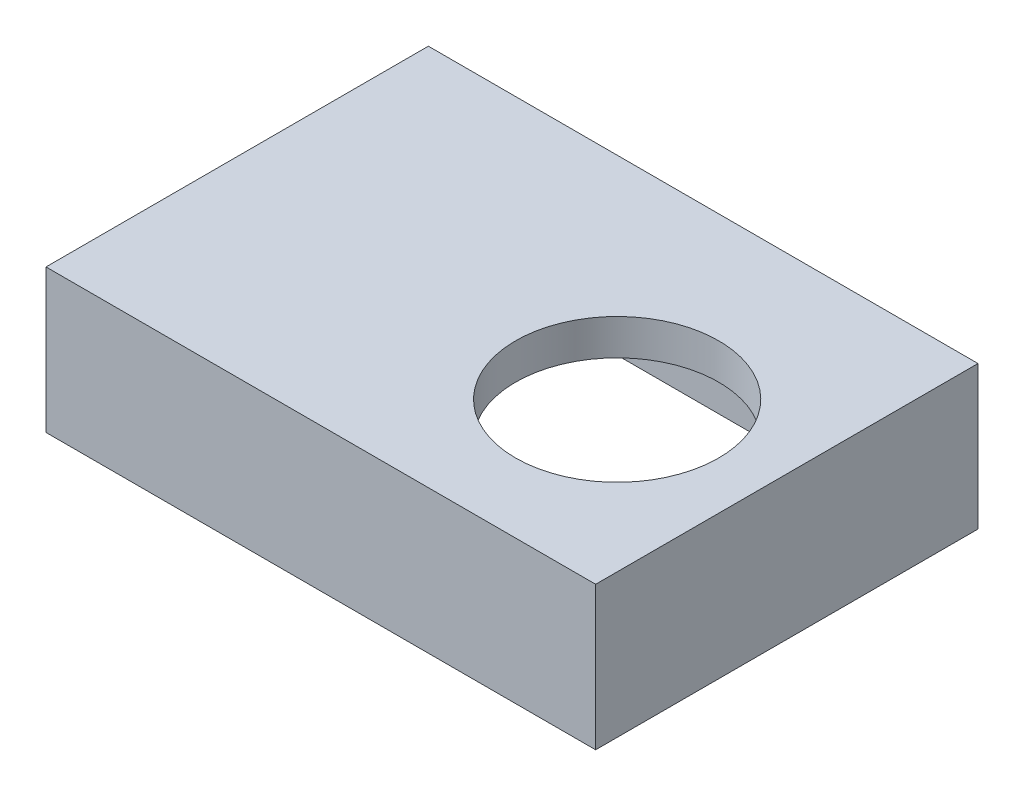
SolidWorks part; units mm, degrees
ref_plane "Front Plane" through (0, 0, 0) normal (0, 0, 1) x (1, 0, 0)
ref_plane "Top Plane" through (0, 0, 0) normal (0, 1, 0) x (1, 0, 0)
ref_plane "Right Plane" through (0, 0, 0) normal (1, 0, 0) x (0, 0, -1)
sketch "Sketch2" plane through (0, 0, 0) normal (0, 1, 0) x (1, 0, 0)
  line L1 (-20, -13) -> (20, -13)
  line L2 (-20, -13) -> (-20, 13)
  line L3 (-20, 13) -> (20, 13)
  line L4 (20, -13) -> (20, 13)
  line L5 (-20, -13) -> (20, 13) construction
  line L6 (-20, 13) -> (20, -13) construction
  point P0 (0, 0)
  dimension "D1" = 40
  dimension "D2" = 26
extrude "Boss-Extrude1" add sketch "Sketch2" along normal blind 3
sketch "Sketch3" plane through (0, 3, 0) normal (0, 1, 0) x (1, 0, 0)
  line L0 (20, -13) -> (20, 13) construction
  line L1 (-20, -13) -> (20, -13) construction
  circle A0 centre (10.5, -1.7) radius 8.5
  dimension "D1" = 17
  dimension "D2" = 9.5
  dimension "D3" = 11.3
extrude "Cut-Extrude1" cut sketch "Sketch3" against normal blind 3
sketch "Sketch4" plane through (20, 0, 0) normal (1, 0, 0) x (0, 0, -1)
  line L1 (13, 0) -> (-13, 0)
  line L2 (13, 0) -> (13, 3)
  line L3 (13, 3) -> (-13, 3)
  line L4 (-13, 0) -> (-13, 3)
extrude "Boss-Extrude2" add sketch "Sketch4" along normal blind 3
sketch "Sketch5" plane through (-20, 0, 0) normal (-1, 0, 0) x (0, 0, 1)
  line L1 (13, 0) -> (-13, 0)
  line L2 (13, 0) -> (13, 3)
  line L3 (13, 3) -> (-13, 3)
  line L4 (-13, 0) -> (-13, 3)
extrude "Boss-Extrude3" add sketch "Sketch5" along normal blind 3
sketch "Sketch6" plane through (0, 0, 13) normal (0, 0, 1) x (1, 0, 0)
  line L1 (23, 0) -> (-23, 0)
  line L2 (23, 0) -> (23, 3)
  line L3 (23, 3) -> (-23, 3)
  line L4 (-23, 0) -> (-23, 3)
extrude "Boss-Extrude4" add sketch "Sketch6" along normal blind 3
sketch "Sketch7" plane through (0, 0, -13) normal (0, 0, -1) x (-1, 0, 0)
  line L1 (23, 0) -> (-23, 0)
  line L2 (23, 0) -> (23, 3)
  line L3 (23, 3) -> (-23, 3)
  line L4 (-23, 0) -> (-23, 3)
extrude "Boss-Extrude5" add sketch "Sketch7" along normal blind 3
sketch "Sketch8" plane through (0, 0, 0) normal (0, -1, 0) x (1, 0, 0)
  line L0 (23, -16) -> (-23, -16) construction
  line L1 (23, 16) -> (20, 16)
  line L2 (23, 16) -> (23, -16)
  line L3 (23, -16) -> (20, -16)
  line L4 (20.5, 13.5) -> (20.5, -13.5)
  line L5 (-23, -16) -> (-23, 16) construction
  line L6 (23, -16) -> (-23, -16)
  line L7 (23, -16) -> (23, -13)
  line L8 (20.5, -13.5) -> (-20.5, -13.5)
  line L9 (-23, -16) -> (-23, -13)
  line L11 (-20, -16) -> (-23, -16)
  line L12 (-20.5, -13.5) -> (-20.5, 13.5)
  line L13 (-20, 16) -> (-23, 16)
  line L14 (-23, -16) -> (-23, 16)
  line L15 (-20.5, 13.5) -> (20.5, 13.5)
  line L16 (-23, 13) -> (-23, 16)
  line L17 (-23, 16) -> (23, 16)
  line L18 (23, 13) -> (23, 16)
  line M10 (-23, 16) -> (-23, -16)
  line M11 (-23, -16) -> (23, -16)
  line M12 (23, -16) -> (23, 16)
  line M13 (23, 16) -> (-23, 16)
  dimension "D1" = 2.5
  dimension "D2" = 2.5
  dimension "D3" = 2.5
  dimension "D4" = 2.5
extrude "Boss-Extrude6" add sketch "Sketch8" along normal blind 9 contours L14 L6 L2 L12 L15 L4 L8 M13 M10 M11 M12
sketch "Sketch9" plane through (0, 0, 0) normal (0, -1, 0) x (1, 0, 0)
  line L0 (20.5, 9.5) -> (16.5, 13.5)
  line L1 (20.5, 13.5) -> (20.5, -13.5) construction
  line L2 (-20.5, 13.5) -> (20.5, 13.5) construction
  line L3 (16.5, 13.5) -> (20.5, 13.5)
  line L4 (20.5, 13.5) -> (20.5, 9.5)
  line L5 (20.5, -5.5) -> (16.5, -13.5)
  line L6 (20.5, -13.5) -> (-20.5, -13.5) construction
  line L7 (16.5, -13.5) -> (20.5, -13.5)
  line L8 (20.5, -13.5) -> (20.5, -5.5)
  dimension "D1" = 4
  dimension "D2" = 4
  dimension "D3" = 8
  dimension "D4" = 4
extrude "Boss-Extrude7" add sketch "Sketch9" along normal blind 6.6
sketch "Sketch10" plane through (-23, 0, 0) normal (-1, 0, 0) x (0, 0, 1)
  line L0 (16, -9) -> (-16, -9) construction
  line L1 (8.2919, -9) -> (-9.3093, -9)
  line L2 (8.2919, -9) -> (8.2919, -3)
  line L3 (8.2919, -3) -> (-9.3093, -3)
  line L4 (-9.3093, -9) -> (-9.3093, -3)
  dimension "D1" = 6
extrude "Cut-Extrude2" cut sketch "Sketch10" against normal blind 6.6
